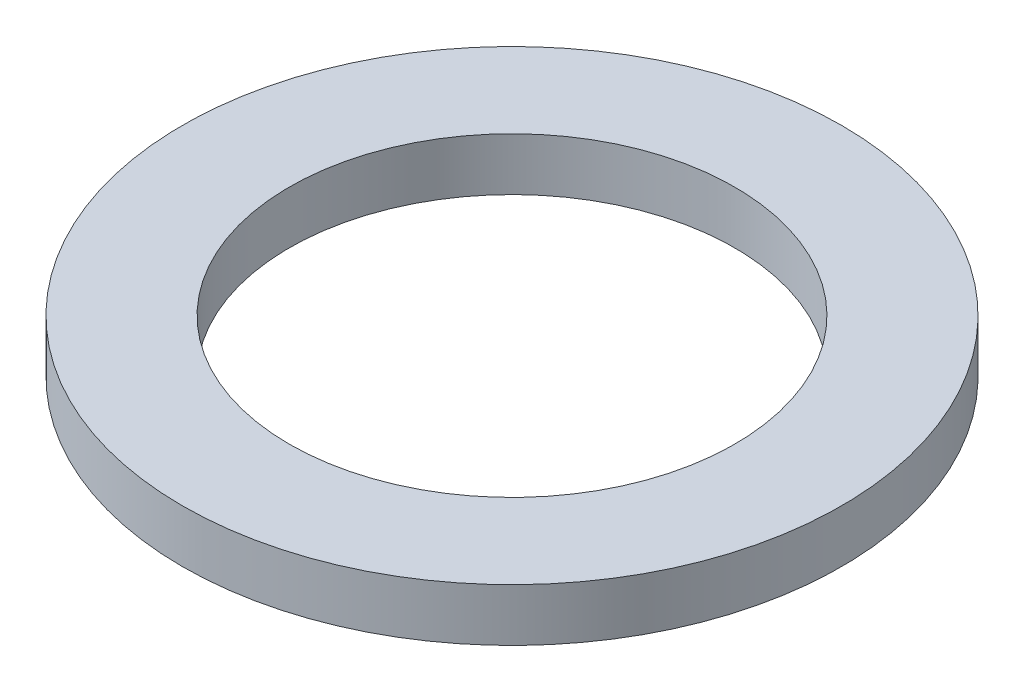
SolidWorks part; units mm, degrees
material "AISI 304"
ref_plane "Front Plane" through (0, 0, 0) normal (0, 0, 1) x (1, 0, 0)
ref_plane "Top Plane" through (0, 0, 0) normal (0, 1, 0) x (1, 0, 0)
ref_plane "Right Plane" through (0, 0, 0) normal (1, 0, 0) x (0, 0, -1)
sketch "Sketch1" plane through (0, 0, 0) normal (0, 1, 0) x (1, 0, 0)
  circle A0 centre (0, 0) radius 5.5626
  dimension "OD" = 11.1252
extrude "Boss-Extrude1" add sketch "Sketch1" along normal blind 0.889
sketch "Sketch5" plane through (0, 0.889, 0) normal (0, 1, 0) x (-1, 0, 0)
  circle A0 centre (0, 0) radius 3.7592
  dimension "ID" = 7.5184
extrude "Cut-Extrude1" cut sketch "Sketch5" against normal through all
